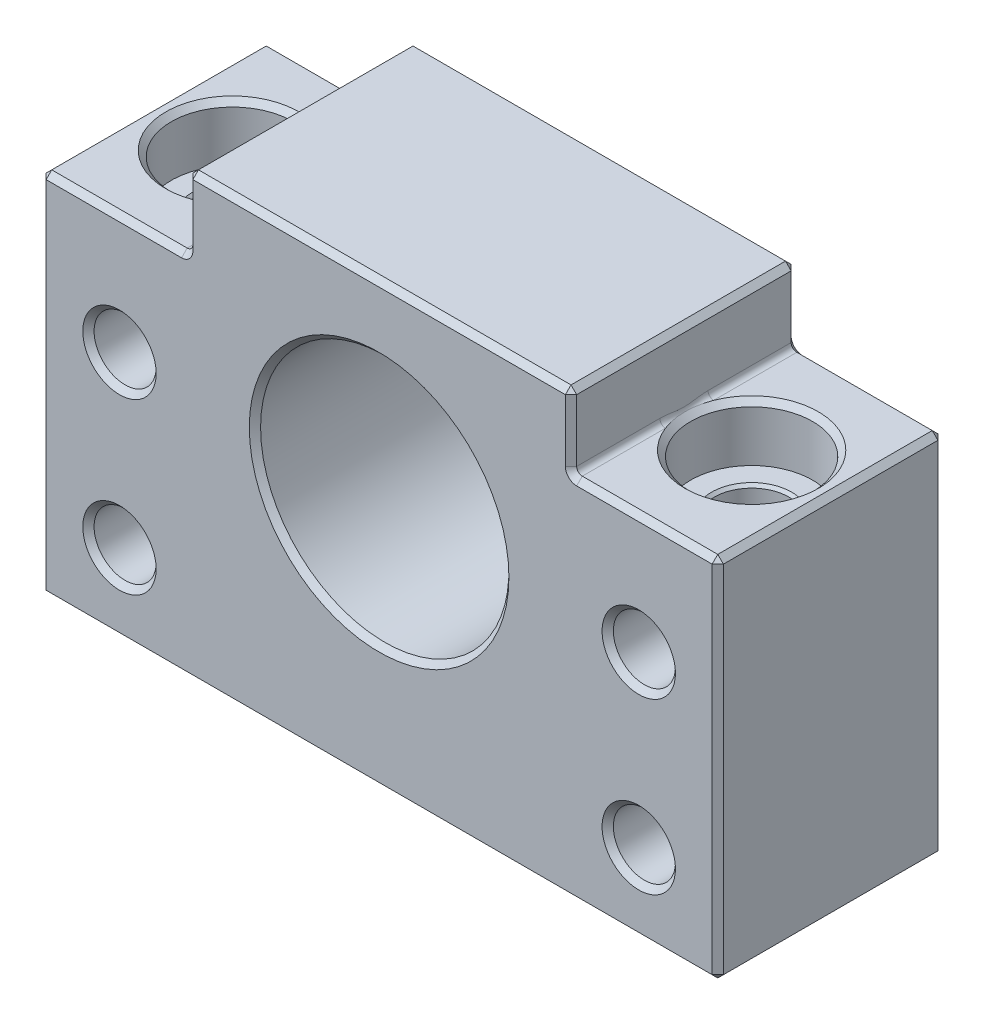
SolidWorks part; units mm, degrees
material "1023 Carbon Steel Sheet (SS)"
ref_plane "Front Plane" through (0, 0, 0) normal (0, 0, 1) x (1, 0, 0)
ref_plane "Top Plane" through (0, 0, 0) normal (0, 1, 0) x (1, 0, 0)
ref_plane "Right Plane" through (0, 0, 0) normal (1, 0, 0) x (0, 0, -1)
sketch "BF Body Sketch" plane through (0, 0, 0) normal (0, 0, 1) x (1, 0, 0)
  line L0 (30, -22) -> (-30, -22)
  line L1 (-30, -22) -> (-30, 10.5)
  line L2 (-30, 10.5) -> (-17, 10.5)
  line L3 (-17, 10.5) -> (-17, 17)
  line L4 (-17, 17) -> (17, 17)
  line L5 (17, 17) -> (17, 10.5)
  line L6 (17, 10.5) -> (30, 10.5)
  line L7 (30, 10.5) -> (30, -22)
  point P2 (0, -22)
  point P3 (0, 17)
  dimension "B" = 60
  dimension "H2" = 22
  dimension "H1" = 32.5
  dimension "B1" = 34
  dimension "H" = 39
extrude "BF Body" add sketch "BF Body Sketch" along normal mid plane 20
sketch "Ball Bearing Hole Sketch" plane through (0, 0, 0) normal (0, 0, 1) x (1, 0, 0)
  circle A4 centre (0, 0) radius 11
  dimension "DO" = 22
extrude "Ball Bearing Hole" cut sketch "Ball Bearing Hole Sketch" against normal through all both and the other way through all
hole_wizard "Vertical Holes" positions "Sketch1" profile "Sketch2" counterbore size "M6" standard "ISO" end condition through all
sketch "Sketch1" plane through (0, 10.5, 0) normal (0, 1, 0) x (1, 0, 0)
  line L0 (23, 0) -> (-23, 0) construction
  point P0 (-23, 0)
  point P2 (23, 0)
  point P9 (0, 0)
  dimension "P" = 46
sketch "Sketch2" plane through (-23, 10.5, 0) normal (1, 0, 0) x (0, 0, 1)
  line L0 (0, 0) -> (0, 32.5)
  line L1 (3.3, 32) -> (3.8, 32.5)
  line L2 (3.3, 32) -> (3.3, 5.25)
  line L3 (3.3, 5.25) -> (3.55, 5)
  line L4 (3.55, 5) -> (5.4, 5)
  line L5 (5.4, 5) -> (5.4, 0.5)
  line L6 (5.4, 0.5) -> (5.9, 0)
  line L7 (5.9, 0) -> (0, 0)
  line L8 (-5.4, 0.5) -> (-5.9, 0) construction
  line L9 (-3.3, 5.25) -> (-3.55, 5) construction
  line L11 (0, -6.35) -> (0, 107.95) construction
  line L12 (3.8, 32.5) -> (0, 32.5)
  line L13 (-3.3, 32) -> (-3.8, 32.5) construction
  dimension "Near C'Sink Angle" = 90
  dimension "Far C'Sink Angle" = 90
  dimension "Thru Hole Dia." = 6.6
  dimension "Thru Hole Depth" = 32.5
  dimension "C'Bore Dia." = 10.8
  dimension "Near C'Sink Dia." = 11.8
  dimension "Mid C'Sink Dia." = 7.1
  dimension "Mid C'Sink Angle" = 90
  dimension "Far C'Sink Dia." = 7.6
hole_wizard "Horizontal Holes" positions "Sketch3" profile "Sketch4" hole size "M5" standard "ISO" end condition through all
sketch "Sketch3" plane through (0, 0, 10) normal (0, 0, 1) x (1, 0, 0)
  line L0 (23, 0) -> (-23, 0) construction
  point P0 (-23, 0)
  point P2 (23, 0)
  point P4 (23, -15)
  point P6 (-23, -15)
  point P12 (0, 0)
  dimension "P" = 46
  dimension "E" = 15
sketch "Sketch4" plane through (-23, 0, 10) normal (1, 0, 0) x (0, -1, 0)
  line L0 (0, 0) -> (0, 20)
  line L1 (0, 20) -> (3.25, 20)
  line L2 (2.75, 19.5) -> (2.75, 0.5)
  line L3 (2.75, 0.5) -> (3.25, 0)
  line L5 (3.25, 0) -> (0, 0)
  line L6 (-2.75, 0.5) -> (-3.25, 0) construction
  line L7 (3.25, 20) -> (2.75, 19.5)
  line L8 (-3.25, 20) -> (-2.75, 19.5) construction
  line L11 (0, -6.35) -> (0, 107.95) construction
  dimension "Thru Hole Dia." = 5.5
  dimension "Thru Hole Depth" = 20
  dimension "Near C'Sink Dia." = 6.5
  dimension "Near C'Sink Angle" = 90
  dimension "Far C'Sink Dia." = 6.5
  dimension "Far C'Sink Angle" = 90
fillet "Production Filet" radius 0.5 2 edges at (-17, 10.5, 0) (17, 10.5, 0)
chamfer "Estetic Chamfer" distance 0.5 angle 45 28 edges at (11, 0, -10) (17, 17, 0) (-17, 17, 0) (30, 10.5, 0) (-30, 10.5, 0) (-30, -22, 0) (23.75, 10.5, -10) (17.1464, 10.6464, -10) (17, 14, -10) (0, 17, -10) (-17, 14, -10) (-17.1464, 10.6464, -10) (-23.75, 10.5, -10) (-30, -5.75, -10) (0, -22, -10) (30, -5.75, -10) (30, -22, 0) (0, -22, 10) (-30, -5.75, 10) (-23.75, 10.5, 10) (-17.1464, 10.6464, 10) (-17, 14, 10) (0, 17, 10) (17, 14, 10) (17.1464, 10.6464, 10) (23.75, 10.5, 10) (30, -5.75, 10) (11, 0, 10)
equation "\"Near C'Sink Dia.@Sketch4\"= \"Thru Hole Dia.@Sketch4\" + 1"
equation "\"Far C'Sink Dia.@Sketch4\"= \"Thru Hole Dia.@Sketch4\" + 1"
equation "\"Near C'Sink Dia.@Sketch2\"= \"C'Bore Dia.@Sketch2\" + 1"
equation "\"Mid C'Sink Dia.@Sketch2\"= \"Thru Hole Dia.@Sketch2\" + 0.5"
equation "\"Far C'Sink Dia.@Sketch2\"= \"Thru Hole Dia.@Sketch2\" + 1"
